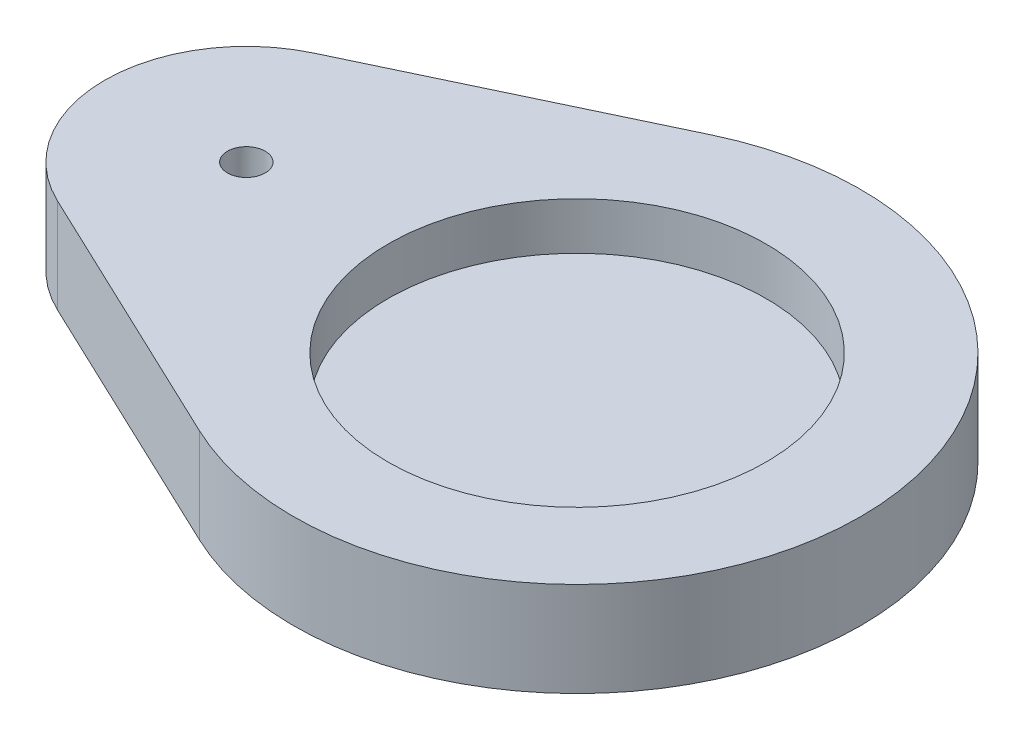
SolidWorks part; units mm, degrees
ref_plane "Front Plane" through (0, 0, 0) normal (0, 0, 1) x (1, 0, 0)
ref_plane "Top Plane" through (0, 0, 0) normal (0, 1, 0) x (1, 0, 0)
ref_plane "Right Plane" through (0, 0, 0) normal (1, 0, 0) x (0, 0, -1)
sketch "Sketch1" plane through (0, 0, 0) normal (0, 1, 0) x (1, 0, 0)
  circle A0 centre (0, 0) radius 40 construction
  circle A1 centre (0, 0) radius 60
  dimension "D1" = 80
  dimension "D2" = 20
extrude "Boss-Extrude1" add sketch "Sketch1" along normal blind 20
sketch "Sketch3" plane through (0, 0, 0) normal (0, 1, 0) x (1, 0, 0)
  line L0 (-70, 0) -> (0, 0) construction
  line L1 (-82.8571, 27.1052) -> (-25.7143, 54.2105)
  line L2 (-82.8571, -27.1052) -> (-25.7143, -54.2105)
  circle A0 centre (-70, 0) radius 20 construction
  arc A1 (-82.8571, 27.1052) -> (-82.8571, -27.1052) centre (-70, 0) ccw
  circle A2 centre (0, 0) radius 60 construction
  circle A3 centre (-70, 0) radius 30 construction
  circle A4 centre (-70, 0) radius 4
  circle A5 centre (0, 0) radius 60
  arc A6 (-25.7143, -54.2105) -> (-25.7143, 54.2105) centre (0, 0) ccw
  dimension "D1" = 40
  dimension "D5" = 8
  dimension "D2" = 70
  dimension "D3" = 10
  dimension "D4" = 0
extrude "Boss-Extrude2" add sketch "Sketch3" along normal blind 20
sketch "Sketch2" plane through (0, 20, 0) normal (0, 1, 0) x (1, 0, 0)
  circle A0 centre (0, 0) radius 40 construction
  circle A1 centre (0, 0) radius 40
extrude "Cut-Extrude1" cut sketch "Sketch2" against normal blind 10
sketch "Sketch4" plane through (0, 0, 0) normal (0, -1, 0) x (1, 0, 0)
  point P0 (0, 0)
sketch "Sketch5" plane through (0, 0, 0) normal (0, -1, 0) x (1, 0, 0)
  circle A2 centre (-70, 0) radius 12
  circle A3 centre (-70, 0) radius 12
  dimension "D1" = 8
extrude "Cut-Extrude2" cut sketch "Sketch5" against normal blind 5
